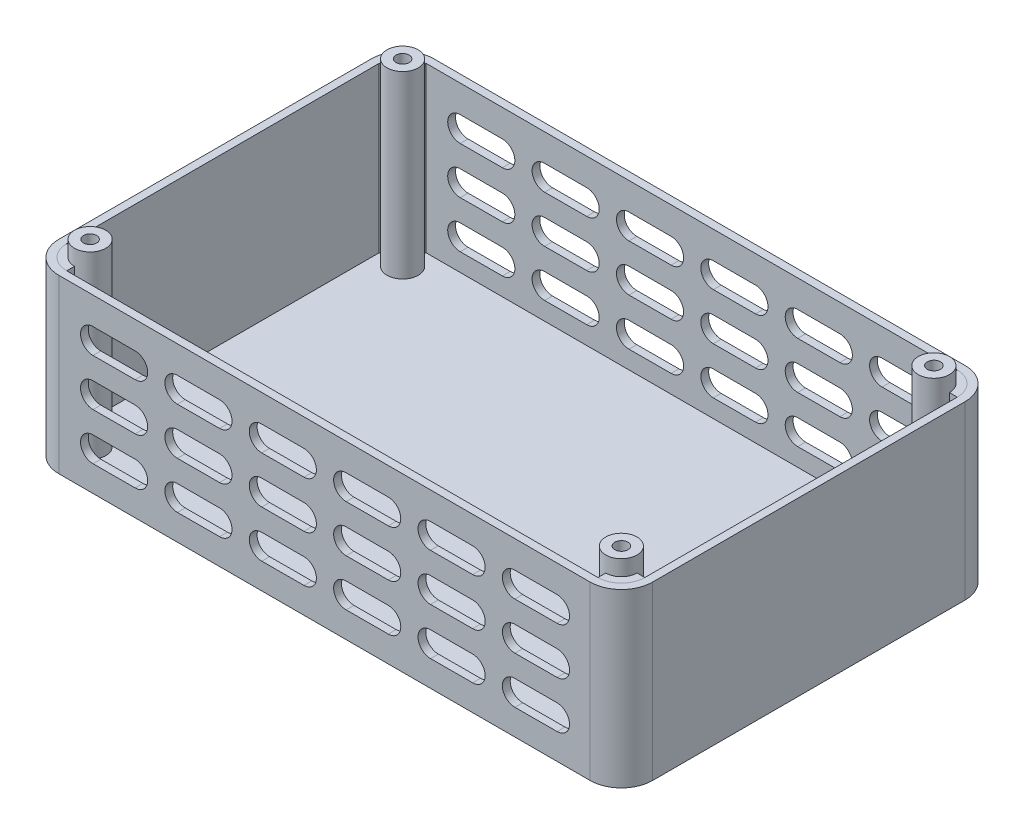
SolidWorks part; units mm, degrees
ref_plane "Front Plane" through (0, 0, 0) normal (0, 0, 1) x (1, 0, 0)
ref_plane "Top Plane" through (0, 0, 0) normal (0, 1, 0) x (1, 0, 0)
ref_plane "Right Plane" through (0, 0, 0) normal (1, 0, 0) x (0, 0, -1)
sketch "Sketch25" plane through (0, 0, 0) normal (0, 1, 0) x (1, 0, 0)
  line L1 (-95.1759, -84.8914) -> (94.8241, -84.8914)
  line L2 (-95.1759, -84.8914) -> (-95.1759, -204.8914)
  line L3 (-95.1759, -204.8914) -> (94.8241, -204.8914)
  line L4 (94.8241, -84.8914) -> (94.8241, -204.8914)
  dimension "D1" = 190
  dimension "D2" = 120
extrude "Boss-Extrude5" add sketch "Sketch25" along normal blind 55 separate body
fillet "Fillet2" radius 10 4 edges at (94.8241, 27.5, 204.8914) (94.8241, 27.5, 84.8914) (-95.1759, 27.5, 204.8914) (-95.1759, 27.5, 84.8914)
shell "Shell4" thickness 2.5
sketch "Sketch26" plane through (0, 2.5, 0) normal (0, 1, 0) x (1, 0, 0)
  circle A0 centre (-85.1759, -94.8914) radius 5
  circle A1 centre (84.8241, -94.8914) radius 5
  circle A2 centre (-85.1759, -194.8914) radius 5
  circle A3 centre (84.8241, -194.8914) radius 5
  dimension "D1" = 10
extrude "Boss-Extrude8" add sketch "Sketch26" along normal blind 57.5
sketch "Sketch29" plane through (0, 2.5, 0) normal (0, 1, 0) x (1, 0, 0)
  line L0 (-85.1759, -87.3914) -> (-85.1759, -94.8914)
  line L1 (-92.6759, -144.8914) -> (119.3528, -144.8914) construction
  line L2 (-92.6759, -94.8914) -> (-85.1759, -94.8914)
  line L3 (-92.6759, -94.8914) -> (-92.6759, -194.8914) construction
  line L4 (-0.1759, -87.3914) -> (-0.1759, -213.9487) construction
  line L5 (84.8241, -87.3914) -> (-85.1759, -87.3914) construction
  line L7 (92.3241, -194.8914) -> (92.3241, -94.8914)
  line L8 (84.8241, -87.3914) -> (-85.1759, -87.3914)
  line L9 (-92.6759, -94.8914) -> (-92.6759, -194.8914)
  line L10 (-85.1759, -202.3914) -> (84.8241, -202.3914)
  line L11 (84.8241, -87.3914) -> (84.8241, -94.8914)
  line L12 (92.3241, -94.8914) -> (84.8241, -94.8914)
  line L13 (92.3241, -194.8914) -> (84.8241, -194.8914)
  line L14 (84.8241, -202.3914) -> (84.8241, -194.8914)
  line L15 (-85.1759, -202.3914) -> (-85.1759, -194.8914)
  line L16 (-92.6759, -194.8914) -> (-85.1759, -194.8914)
  arc A0 (-85.1759, -87.3914) -> (-92.6759, -94.8914) centre (-85.1759, -94.8914) ccw construction
  arc A3 (84.8241, -87.3914) -> (92.3241, -94.8914) centre (84.8241, -94.8914) cw
  arc A4 (84.8241, -202.3914) -> (92.3241, -194.8914) centre (84.8241, -194.8914) ccw
  arc A5 (-85.1759, -202.3914) -> (-92.6759, -194.8914) centre (-85.1759, -194.8914) cw
  arc A7 (92.3241, -94.8914) -> (84.8241, -87.3914) centre (84.8241, -94.8914) ccw
  arc A8 (-85.1759, -87.3914) -> (-92.6759, -94.8914) centre (-85.1759, -94.8914) ccw
  arc A9 (-92.6759, -194.8914) -> (-85.1759, -202.3914) centre (-85.1759, -194.8914) ccw
  arc A10 (84.8241, -202.3914) -> (92.3241, -194.8914) centre (84.8241, -194.8914) ccw
  arc A12 (-85.1759, -87.3914) -> (-92.6759, -94.8914) centre (-85.1759, -94.8914) ccw
  dimension "D1" = 0
extrude "Boss-Extrude9" add sketch "Sketch29" along normal up to surface (52.5 mm away) separate body up to face at (-0.1759, 55, 144.8914)
sketch "Sketch32" plane through (0, 0, 204.8914) normal (0, 0, 1) x (1, 0, 0)
  line L2 (-74.2499, 38.2538) -> (-60.75, 38.2918)
  line L3 (-60.75, 46.2538) -> (-74.25, 46.2538)
  line L4 (-33.75, 46.2538) -> (-47.25, 46.2538)
  line L5 (-47.2499, 38.2538) -> (-33.75, 38.2918)
  line L6 (-6.75, 46.2538) -> (-20.25, 46.2538)
  line L7 (-20.2499, 38.2538) -> (-6.75, 38.2918)
  line L8 (20.25, 46.2538) -> (6.75, 46.2538)
  line L9 (6.7501, 38.2538) -> (20.25, 38.2918)
  line L10 (47.25, 46.2538) -> (33.75, 46.2538)
  line L11 (33.7501, 38.2538) -> (47.25, 38.2918)
  line L12 (74.25, 46.2538) -> (60.75, 46.2538)
  line L13 (60.7501, 38.2538) -> (74.25, 38.2918)
  line L14 (-33.75, 31.2538) -> (-47.25, 31.2538)
  line L15 (-47.2499, 23.2538) -> (-33.75, 23.2918)
  line L16 (-6.75, 31.2538) -> (-20.25, 31.2538)
  line L17 (-20.2499, 23.2538) -> (-6.75, 23.2918)
  line L18 (20.25, 31.2538) -> (6.75, 31.2538)
  line L19 (6.7501, 23.2538) -> (20.25, 23.2918)
  line L20 (47.25, 31.2538) -> (33.75, 31.2538)
  line L21 (33.7501, 23.2538) -> (47.25, 23.2918)
  line L22 (74.25, 31.2538) -> (60.75, 31.2538)
  line L23 (60.7501, 23.2538) -> (74.25, 23.2918)
  line L24 (-33.75, 16.2538) -> (-47.25, 16.2538)
  line L25 (-47.2499, 8.2538) -> (-33.75, 8.2918)
  line L26 (-6.75, 16.2538) -> (-20.25, 16.2538)
  line L27 (-20.2499, 8.2538) -> (-6.75, 8.2918)
  line L28 (20.25, 16.2538) -> (6.75, 16.2538)
  line L29 (6.7501, 8.2538) -> (20.25, 8.2918)
  line L30 (47.25, 16.2538) -> (33.75, 16.2538)
  line L31 (33.7501, 8.2538) -> (47.25, 8.2918)
  line L32 (74.25, 16.2538) -> (60.75, 16.2538)
  line L33 (60.7501, 8.2538) -> (74.25, 8.2918)
  line L34 (-60.75, 31.2538) -> (-74.25, 31.2538)
  line L35 (-74.2499, 23.2538) -> (-60.75, 23.2918)
  line L36 (-60.75, 16.2538) -> (-74.25, 16.2538)
  line L37 (-74.2499, 8.2538) -> (-60.75, 8.2918)
  arc A2 (-60.75, 38.2918) -> (-60.75, 46.2538) centre (-60.75, 42.2728) ccw
  arc A3 (-74.25, 46.2538) -> (-74.2499, 38.2538) centre (-74.25, 42.2538) ccw
  arc A4 (-33.75, 38.2918) -> (-33.75, 46.2538) centre (-33.75, 42.2728) ccw
  arc A5 (-47.25, 46.2538) -> (-47.2499, 38.2538) centre (-47.25, 42.2538) ccw
  arc A6 (-6.75, 38.2918) -> (-6.75, 46.2538) centre (-6.75, 42.2728) ccw
  arc A7 (-20.25, 46.2538) -> (-20.2499, 38.2538) centre (-20.25, 42.2538) ccw
  arc A8 (20.25, 38.2918) -> (20.25, 46.2538) centre (20.25, 42.2728) ccw
  arc A9 (6.75, 46.2538) -> (6.7501, 38.2538) centre (6.75, 42.2538) ccw
  arc A10 (47.25, 38.2918) -> (47.25, 46.2538) centre (47.25, 42.2728) ccw
  arc A11 (33.75, 46.2538) -> (33.7501, 38.2538) centre (33.75, 42.2538) ccw
  arc A12 (74.25, 38.2918) -> (74.25, 46.2538) centre (74.25, 42.2728) ccw
  arc A13 (60.75, 46.2538) -> (60.7501, 38.2538) centre (60.75, 42.2538) ccw
  arc A14 (-33.75, 23.2918) -> (-33.75, 31.2538) centre (-33.75, 27.2728) ccw
  arc A15 (-47.25, 31.2538) -> (-47.2499, 23.2538) centre (-47.25, 27.2538) ccw
  arc A16 (-6.75, 23.2918) -> (-6.75, 31.2538) centre (-6.75, 27.2728) ccw
  arc A17 (-20.25, 31.2538) -> (-20.2499, 23.2538) centre (-20.25, 27.2538) ccw
  arc A18 (20.25, 23.2918) -> (20.25, 31.2538) centre (20.25, 27.2728) ccw
  arc A19 (6.75, 31.2538) -> (6.7501, 23.2538) centre (6.75, 27.2538) ccw
  arc A20 (47.25, 23.2918) -> (47.25, 31.2538) centre (47.25, 27.2728) ccw
  arc A21 (33.75, 31.2538) -> (33.7501, 23.2538) centre (33.75, 27.2538) ccw
  arc A22 (74.25, 23.2918) -> (74.25, 31.2538) centre (74.25, 27.2728) ccw
  arc A23 (60.75, 31.2538) -> (60.7501, 23.2538) centre (60.75, 27.2538) ccw
  arc A24 (-33.75, 8.2918) -> (-33.75, 16.2538) centre (-33.75, 12.2728) ccw
  arc A25 (-47.25, 16.2538) -> (-47.2499, 8.2538) centre (-47.25, 12.2538) ccw
  arc A26 (-6.75, 8.2918) -> (-6.75, 16.2538) centre (-6.75, 12.2728) ccw
  arc A27 (-20.25, 16.2538) -> (-20.2499, 8.2538) centre (-20.25, 12.2538) ccw
  arc A28 (20.25, 8.2918) -> (20.25, 16.2538) centre (20.25, 12.2728) ccw
  arc A29 (6.75, 16.2538) -> (6.7501, 8.2538) centre (6.75, 12.2538) ccw
  arc A30 (47.25, 8.2918) -> (47.25, 16.2538) centre (47.25, 12.2728) ccw
  arc A31 (33.75, 16.2538) -> (33.7501, 8.2538) centre (33.75, 12.2538) ccw
  arc A32 (74.25, 8.2918) -> (74.25, 16.2538) centre (74.25, 12.2728) ccw
  arc A33 (60.75, 16.2538) -> (60.7501, 8.2538) centre (60.75, 12.2538) ccw
  arc A34 (-60.75, 23.2918) -> (-60.75, 31.2538) centre (-60.75, 27.2728) ccw
  arc A35 (-74.25, 31.2538) -> (-74.2499, 23.2538) centre (-74.25, 27.2538) ccw
  arc A36 (-60.75, 8.2918) -> (-60.75, 16.2538) centre (-60.75, 12.2728) ccw
  arc A37 (-74.25, 16.2538) -> (-74.2499, 8.2538) centre (-74.25, 12.2538) ccw
  dimension "D1" = 3
extrude "Cut-Extrude3" cut sketch "Sketch32" against normal blind 3
sketch "Sketch34" plane through (0, 0, 84.8914) normal (0, 0, -1) x (-1, 0, 0)
  line L0 (-74.25, 38.2918) -> (-60.7501, 38.2538) construction
  line L1 (-60.75, 46.2538) -> (-74.25, 46.2538) construction
  line L2 (-74.25, 38.2918) -> (-60.7501, 38.2538)
  line L3 (-60.75, 46.2538) -> (-74.25, 46.2538)
  line L4 (-33.75, 46.2538) -> (-47.25, 46.2538)
  line L5 (-47.25, 38.2918) -> (-33.7501, 38.2538)
  line L6 (-6.75, 46.2538) -> (-20.25, 46.2538)
  line L7 (-20.25, 38.2918) -> (-6.7501, 38.2538)
  line L8 (20.25, 46.2538) -> (6.75, 46.2538)
  line L9 (6.75, 38.2918) -> (20.2499, 38.2538)
  line L10 (47.25, 46.2538) -> (33.75, 46.2538)
  line L11 (33.75, 38.2918) -> (47.2499, 38.2538)
  line L12 (74.25, 46.2538) -> (60.75, 46.2538)
  line L13 (60.75, 38.2918) -> (74.2499, 38.2538)
  line L14 (-33.75, 31.2538) -> (-47.25, 31.2538)
  line L15 (-47.25, 23.2918) -> (-33.7501, 23.2538)
  line L16 (-6.75, 31.2538) -> (-20.25, 31.2538)
  line L17 (-20.25, 23.2918) -> (-6.7501, 23.2538)
  line L18 (20.25, 31.2538) -> (6.75, 31.2538)
  line L19 (6.75, 23.2918) -> (20.2499, 23.2538)
  line L20 (47.25, 31.2538) -> (33.75, 31.2538)
  line L21 (33.75, 23.2918) -> (47.2499, 23.2538)
  line L22 (74.25, 31.2538) -> (60.75, 31.2538)
  line L23 (60.75, 23.2918) -> (74.2499, 23.2538)
  line L24 (-33.75, 16.2538) -> (-47.25, 16.2538)
  line L25 (-47.25, 8.2918) -> (-33.7501, 8.2538)
  line L26 (-6.75, 16.2538) -> (-20.25, 16.2538)
  line L27 (-20.25, 8.2918) -> (-6.7501, 8.2538)
  line L28 (20.25, 16.2538) -> (6.75, 16.2538)
  line L29 (6.75, 8.2918) -> (20.2499, 8.2538)
  line L30 (47.25, 16.2538) -> (33.75, 16.2538)
  line L31 (33.75, 8.2918) -> (47.2499, 8.2538)
  line L32 (74.25, 16.2538) -> (60.75, 16.2538)
  line L33 (60.75, 8.2918) -> (74.2499, 8.2538)
  line L34 (-60.75, 31.2538) -> (-74.25, 31.2538)
  line L35 (-74.25, 23.2918) -> (-60.7501, 23.2538)
  line L36 (-60.75, 16.2538) -> (-74.25, 16.2538)
  line L37 (-74.25, 8.2918) -> (-60.7501, 8.2538)
  arc A0 (-60.7501, 38.2538) -> (-60.75, 46.2538) centre (-60.75, 42.2538) ccw construction
  arc A1 (-74.25, 46.2538) -> (-74.25, 38.2918) centre (-74.25, 42.2728) ccw construction
  arc A2 (-60.7501, 38.2538) -> (-60.75, 46.2538) centre (-60.75, 42.2538) ccw
  arc A3 (-74.25, 46.2538) -> (-74.25, 38.2918) centre (-74.25, 42.2728) ccw
  arc A4 (-33.7501, 38.2538) -> (-33.75, 46.2538) centre (-33.75, 42.2538) ccw
  arc A5 (-47.25, 46.2538) -> (-47.25, 38.2918) centre (-47.25, 42.2728) ccw
  arc A6 (-6.7501, 38.2538) -> (-6.75, 46.2538) centre (-6.75, 42.2538) ccw
  arc A7 (-20.25, 46.2538) -> (-20.25, 38.2918) centre (-20.25, 42.2728) ccw
  arc A8 (20.2499, 38.2538) -> (20.25, 46.2538) centre (20.25, 42.2538) ccw
  arc A9 (6.75, 46.2538) -> (6.75, 38.2918) centre (6.75, 42.2728) ccw
  arc A10 (47.2499, 38.2538) -> (47.25, 46.2538) centre (47.25, 42.2538) ccw
  arc A11 (33.75, 46.2538) -> (33.75, 38.2918) centre (33.75, 42.2728) ccw
  arc A12 (74.2499, 38.2538) -> (74.25, 46.2538) centre (74.25, 42.2538) ccw
  arc A13 (60.75, 46.2538) -> (60.75, 38.2918) centre (60.75, 42.2728) ccw
  arc A14 (-33.7501, 23.2538) -> (-33.75, 31.2538) centre (-33.75, 27.2538) ccw
  arc A15 (-47.25, 31.2538) -> (-47.25, 23.2918) centre (-47.25, 27.2728) ccw
  arc A16 (-6.7501, 23.2538) -> (-6.75, 31.2538) centre (-6.75, 27.2538) ccw
  arc A17 (-20.25, 31.2538) -> (-20.25, 23.2918) centre (-20.25, 27.2728) ccw
  arc A18 (20.2499, 23.2538) -> (20.25, 31.2538) centre (20.25, 27.2538) ccw
  arc A19 (6.75, 31.2538) -> (6.75, 23.2918) centre (6.75, 27.2728) ccw
  arc A20 (47.2499, 23.2538) -> (47.25, 31.2538) centre (47.25, 27.2538) ccw
  arc A21 (33.75, 31.2538) -> (33.75, 23.2918) centre (33.75, 27.2728) ccw
  arc A22 (74.2499, 23.2538) -> (74.25, 31.2538) centre (74.25, 27.2538) ccw
  arc A23 (60.75, 31.2538) -> (60.75, 23.2918) centre (60.75, 27.2728) ccw
  arc A24 (-33.7501, 8.2538) -> (-33.75, 16.2538) centre (-33.75, 12.2538) ccw
  arc A25 (-47.25, 16.2538) -> (-47.25, 8.2918) centre (-47.25, 12.2728) ccw
  arc A26 (-6.7501, 8.2538) -> (-6.75, 16.2538) centre (-6.75, 12.2538) ccw
  arc A27 (-20.25, 16.2538) -> (-20.25, 8.2918) centre (-20.25, 12.2728) ccw
  arc A28 (20.2499, 8.2538) -> (20.25, 16.2538) centre (20.25, 12.2538) ccw
  arc A29 (6.75, 16.2538) -> (6.75, 8.2918) centre (6.75, 12.2728) ccw
  arc A30 (47.2499, 8.2538) -> (47.25, 16.2538) centre (47.25, 12.2538) ccw
  arc A31 (33.75, 16.2538) -> (33.75, 8.2918) centre (33.75, 12.2728) ccw
  arc A32 (74.2499, 8.2538) -> (74.25, 16.2538) centre (74.25, 12.2538) ccw
  arc A33 (60.75, 16.2538) -> (60.75, 8.2918) centre (60.75, 12.2728) ccw
  arc A34 (-60.7501, 23.2538) -> (-60.75, 31.2538) centre (-60.75, 27.2538) ccw
  arc A35 (-74.25, 31.2538) -> (-74.25, 23.2918) centre (-74.25, 27.2728) ccw
  arc A36 (-60.7501, 8.2538) -> (-60.75, 16.2538) centre (-60.75, 12.2538) ccw
  arc A37 (-74.25, 16.2538) -> (-74.25, 8.2918) centre (-74.25, 12.2728) ccw
  dimension "D1" = 3
extrude "Cut-Extrude4" cut sketch "Sketch34" against normal blind 3
hole_wizard "Tap Drill for M5 Tap1" positions "Sketch35" profile "Sketch36" hole size "M5" standard "ISO"
sketch "Sketch35" plane through (0, 60, 0) normal (0, 1, 0) x (1, 0, 0)
  point P0 (-85.1759, -94.8914)
  point P3 (-85.1759, -194.8914)
  point P6 (84.8241, -94.8914)
  point P9 (84.8241, -194.8914)
sketch "Sketch36" plane through (-85.1759, 60, 94.8914) normal (1, 0, 0) x (0, 0, 1)
  line L0 (0, 0) -> (0, 21.2618)
  line L1 (0, 21.2618) -> (2.1, 20)
  line L2 (2.1, 20) -> (2.1, 0)
  line L5 (2.1, 0) -> (0, 0)
  line L10 (0, 21.2618) -> (-2.1, 20) construction
  line L11 (0, -6.35) -> (0, 107.95) construction
  dimension "Hole Dia." = 4.2
  dimension "Hole Depth" = 20
  dimension "Drill Angle" = 118
